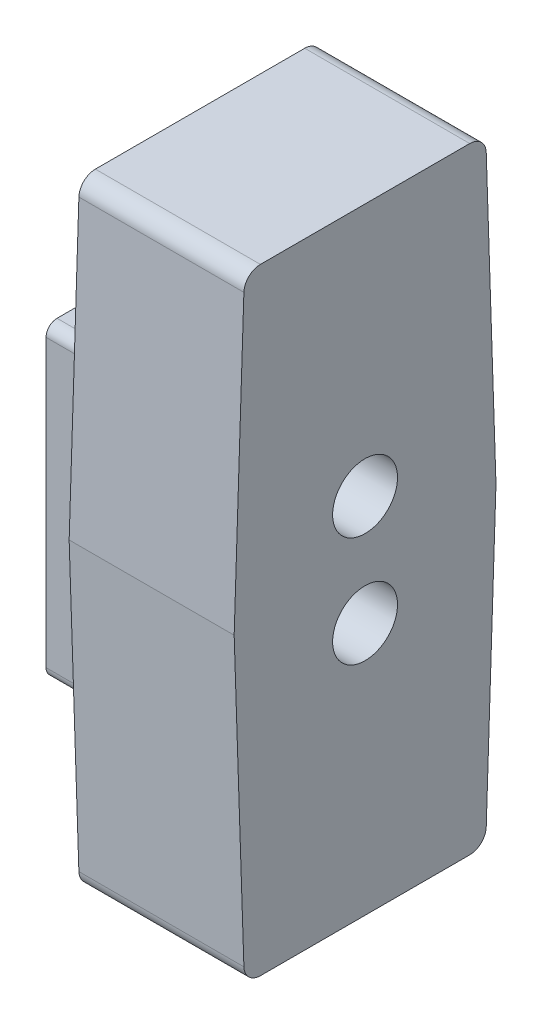
SolidWorks part; units mm, degrees
material "UHMW"
ref_plane "Front Plane" through (0, 0, 0) normal (0, 0, 1) x (1, 0, 0)
ref_plane "Top Plane" through (0, 0, 0) normal (0, 1, 0) x (1, 0, 0)
ref_plane "Right Plane" through (0, 0, 0) normal (1, 0, 0) x (0, 0, -1)
sketch "Sketch1" plane through (0, 0, 0) normal (1, 0, 0) x (0, 0, -1)
  line L6 (0.3808, -13.4747) -> (0.6056, -6.731)
  line L7 (0.6056, -6.731) -> (0.3808, 0.0127)
  line L8 (0, 0.381) -> (-4.8335, 0.381)
  line L9 (-5.2143, 0.0127) -> (-5.4391, -6.731)
  line L10 (-5.4391, -6.731) -> (-5.2143, -13.4747)
  line L11 (-4.8335, -13.843) -> (0, -13.843)
  arc A4 (0.3808, 0.0127) -> (0, 0.381) centre (0, 0) ccw
  arc A5 (-4.8335, 0.381) -> (-5.2143, 0.0127) centre (-4.8335, 0) ccw
  arc A6 (-5.2143, -13.4747) -> (-4.8335, -13.843) centre (-4.8335, -13.462) ccw
  arc A7 (0, -13.843) -> (0.3808, -13.4747) centre (0, -13.462) ccw
extrude "Boss-Extrude1" add sketch "Sketch1" along normal blind 3.81
sketch "Sketch2" plane through (0, 0, 0) normal (-1, 0, 0) x (0, 0, 1)
  line L0 (2.4168, 0.381) -> (2.4168, -13.843) construction
  line L1 (0, 0.381) -> (4.8335, 0.381) construction
  line L2 (4.8335, -13.843) -> (0, -13.843) construction
  line L3 (-0.6056, -6.731) -> (5.4391, -6.731) construction
hole_wizard "CSK for #0 Flat Head Machine Screw (100)1" positions "Sketch4" profile "Sketch3" countersink size "#0" standard "ANSI Inch"
sketch "Sketch4" plane through (0, 0, 0) normal (-1, 0, 0) x (0, 0, 1)
  line L0 (2.4168, -1.5807) -> (2.4168, -5.0142) construction
  line L1 (2.4168, -5.0142) -> (2.4168, -8.4478) construction
  line L4 (2.4168, -8.4478) -> (2.4168, -11.8813) construction
  line L6 (-0.6056, -6.731) -> (5.4391, -6.731) construction
  line L7 (2.4168, 0.381) -> (2.4168, -13.843) construction
  line L8 (2.4168, -11.8813) -> (2.4168, -13.843) construction
  line L10 (2.4168, 0.381) -> (2.4168, -1.5807) construction
  point P0 (2.4168, -1.5807)
  point P2 (2.4168, -5.0142)
  point P6 (2.4168, -8.4478)
  point P8 (2.4168, -11.8813)
sketch "Sketch3" plane through (0, -1.5807, 2.4168) normal (0, 1, 0) x (0, 0, 1)
  line L0 (0, 0) -> (0, 2.54)
  line L1 (0, 2.54) -> (0.635, 2.54)
  line L2 (0.635, 2.54) -> (0.635, 0.5588)
  line L3 (0.635, 0.5588) -> (1.0795, 0)
  line L5 (1.0795, 0) -> (0, 0)
  line L6 (-0.635, 0.5588) -> (-1.0795, 0) construction
  line L11 (0, -6.35) -> (0, 107.95) construction
  dimension "Thru Hole Dia." = 1.27
  dimension "Thru Hole Depth" = 2.54
  dimension "Near C'Sink Dia." = 2.159
  dimension "Near C'Sink Angle" = 77
sketch "Sketch5" plane through (0, 0, 0) normal (-1, 0, 0) x (0, 0, 1)
  line L0 (0.1308, -10.287) -> (4.7028, -10.287)
  line L1 (4.9568, -10.033) -> (4.9568, -3.429)
  line L2 (-0.6056, -6.731) -> (5.4391, -6.731) construction
  line L3 (2.4168, 0.381) -> (2.4168, -13.843) construction
  line L5 (2.4168, -13.843) -> (2.4168, -10.287) construction
  line L6 (2.4168, -10.287) -> (2.4168, -6.731) construction
  line L7 (-0.1232, -10.033) -> (-0.1232, -3.429)
  line L8 (-0.1232, -6.731) -> (4.9568, -6.731) construction
  line L9 (0.1308, -3.175) -> (4.7028, -3.175)
  arc A0 (-0.1232, -10.033) -> (0.1308, -10.287) centre (0.1308, -10.033) ccw
  arc A1 (0.1308, -3.175) -> (-0.1232, -3.429) centre (0.1308, -3.429) ccw
  arc A2 (4.7028, -3.175) -> (4.9568, -3.429) centre (4.7028, -3.429) cw
  arc A3 (4.7028, -10.287) -> (4.9568, -10.033) centre (4.7028, -10.033) ccw
  dimension "D2" = 0.254
  dimension "D3" = 0.254
  dimension "D1" = 2.54
extrude "Boss-Extrude2" add sketch "Sketch5" along normal blind 1.016
sketch "Sketch6" plane through (-1.016, 0, 0) normal (-1, 0, 0) x (0, 0, 1)
  line L0 (2.4168, 0.381) -> (2.4168, -13.843) construction
  line L1 (2.4168, -3.175) -> (2.4168, -5.461) construction
  line L2 (4.7028, -3.175) -> (0.1308, -3.175) construction
  line L3 (2.4168, -5.461) -> (2.4168, -8.001) construction
  line L4 (2.4168, -8.001) -> (2.4168, -10.287) construction
  line L5 (0.1308, -10.287) -> (4.7028, -10.287) construction
  circle A0 centre (2.4168, -5.461) radius 0.75
  circle A1 centre (2.4168, -8.001) radius 0.75
  point P7 (0, 0)
  point P13 (0, 0)
  point P14 (0, 0)
  dimension "D1" = 2.54
  dimension "D2" = 1.5
extrude "Cut-Extrude1" cut sketch "Sketch6" against normal through all both and the other way through all
